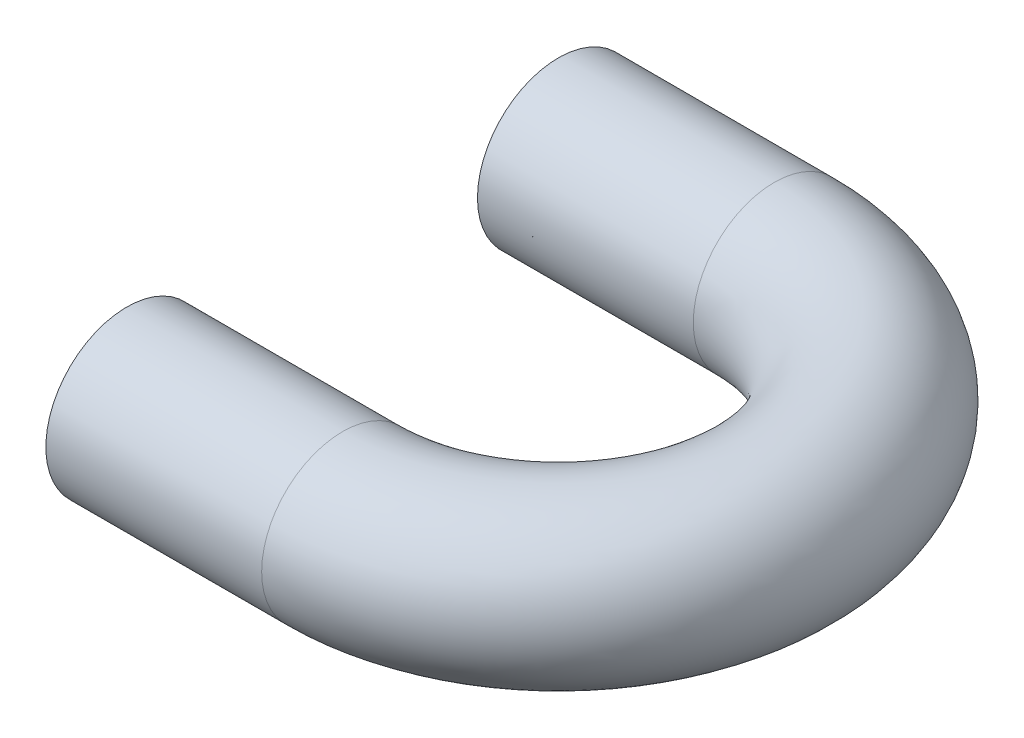
SolidWorks part; units mm, degrees
ref_plane "前视基准面" through (0, 0, 0) normal (0, 0, 1) x (1, 0, 0)
ref_plane "上视基准面" through (0, 0, 0) normal (0, 1, 0) x (1, 0, 0)
ref_plane "右视基准面" through (0, 0, 0) normal (1, 0, 0) x (0, 0, -1)
sketch "草图1" plane through (0, 0, 0) normal (1, 0, 0) x (0, 0, -1)
  circle A0 centre (0, 0) radius 5.7
  circle A1 centre (0, 0) radius 7.5
  dimension "D1" = 15
  dimension "D2" = 11.4
sketch "草图2" plane through (0, 0, 0) normal (0, 1, 0) x (1, 0, 0)
  line L0 (0, 0) -> (20, 0)
  line L1 (0, -5.7) -> (0, 5.7) construction
  line L2 (20, 40) -> (0, 40)
  arc A0 (20, 0) -> (20, 40) centre (20, 20) ccw
  dimension "D3" = 20
  dimension "D1" = 20
  dimension "D2" = 20
sweep "扫描1" add profiles "草图1" path "草图2"
